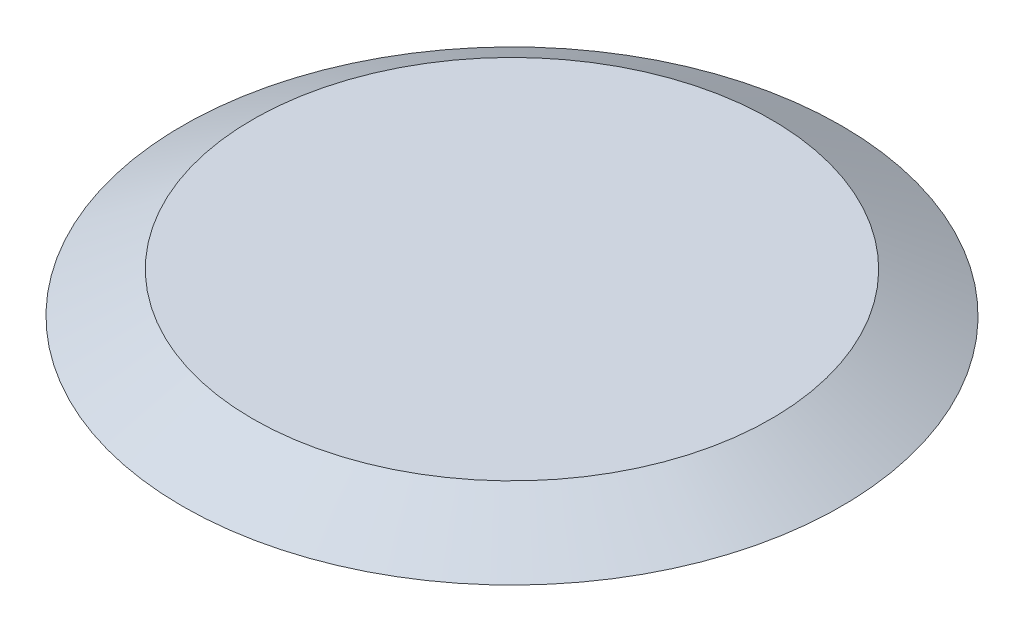
SolidWorks part; units mm, degrees
ref_plane "Front Plane" through (0, 0, 0) normal (0, 0, 1) x (1, 0, 0)
ref_plane "Top Plane" through (0, 0, 0) normal (0, 1, 0) x (1, 0, 0)
ref_plane "Right Plane" through (0, 0, 0) normal (1, 0, 0) x (0, 0, -1)
sketch "Sketch1" plane through (0, 0, 0) normal (0, 1, 0) x (1, 0, 0)
  circle A0 centre (0, 0) radius 8.255
  dimension "D1" = 16.51
extrude "Boss-Extrude1" add sketch "Sketch1" along normal blind 1.016 draft 60
